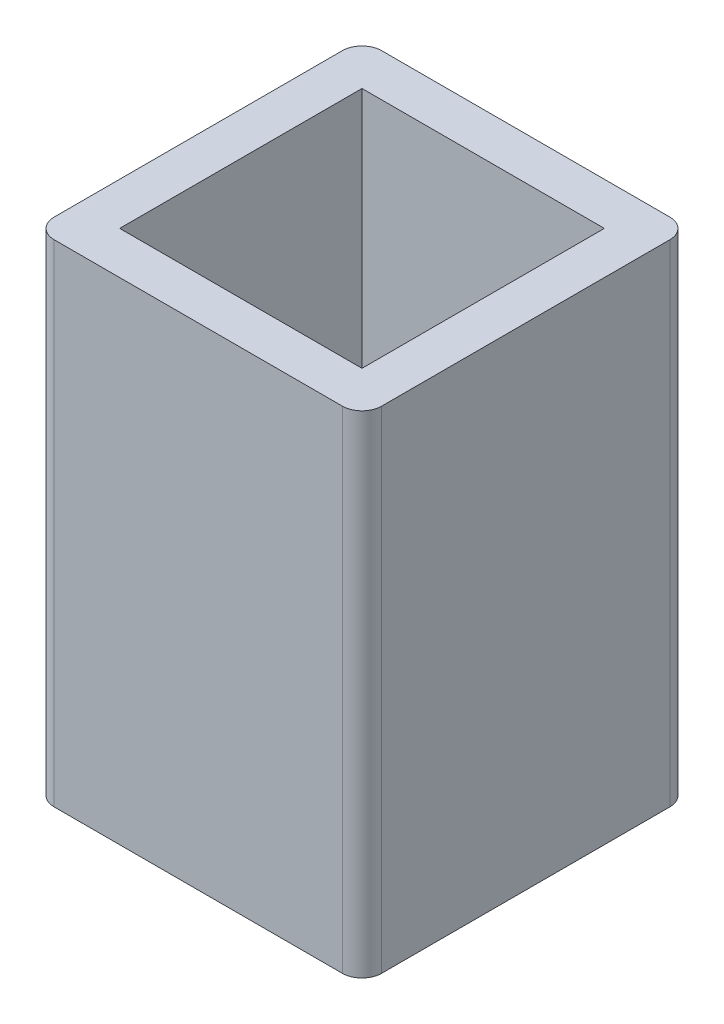
SolidWorks part; units mm, degrees
material "Plain Carbon Steel"
ref_plane "Front Plane" through (0, 0, 0) normal (0, 0, 1) x (1, 0, 0)
ref_plane "Top Plane" through (0, 0, 0) normal (0, 1, 0) x (1, 0, 0)
ref_plane "Right Plane" through (0, 0, 0) normal (1, 0, 0) x (0, 0, -1)
sketch "Sketch1" plane through (0, 0, 0) normal (0, 1, 0) x (1, 0, 0)
  line L1 (-5.588, -6.35) -> (5.588, -6.35)
  line L2 (-6.35, -5.588) -> (-6.35, 5.588)
  line L3 (-5.588, 6.35) -> (5.588, 6.35)
  line L4 (6.35, -5.588) -> (6.35, 5.588)
  line L5 (0, 6.35) -> (0, -6.35) construction
  line L6 (-6.35, 0) -> (6.35, 0) construction
  line L10 (-4.699, -4.699) -> (-4.699, 4.699)
  line L11 (-4.699, 4.699) -> (4.699, 4.699)
  line L12 (4.699, -4.699) -> (4.699, 4.699)
  line L13 (-4.699, -4.699) -> (4.699, -4.699)
  arc A0 (-5.588, -6.35) -> (-6.35, -5.588) centre (-5.588, -5.588) cw
  arc A1 (5.588, -6.35) -> (6.35, -5.588) centre (5.588, -5.588) ccw
  arc A2 (5.588, 6.35) -> (6.35, 5.588) centre (5.588, 5.588) cw
  arc A3 (-6.35, 5.588) -> (-5.588, 6.35) centre (-5.588, 5.588) cw
  arc A8 (-4.699, 4.699) -> (-4.699, 4.699) centre (-4.699, 4.699) cw
  arc A9 (4.699, 4.699) -> (4.699, 4.699) centre (4.699, 4.699) cw
  arc A10 (4.699, -4.699) -> (4.699, -4.699) centre (4.699, -4.699) ccw
  arc A11 (-4.699, -4.699) -> (-4.699, -4.699) centre (-4.699, -4.699) cw
  point P0 (0, 0)
  point P11 (6.35, 6.35)
  point P14 (-6.35, 6.35)
  dimension "D2" = 0.762
  dimension "D1" = 12.7
  dimension "D3" = 1.651
extrude "Boss-Extrude1" add sketch "Sketch1" along normal blind 19.05
